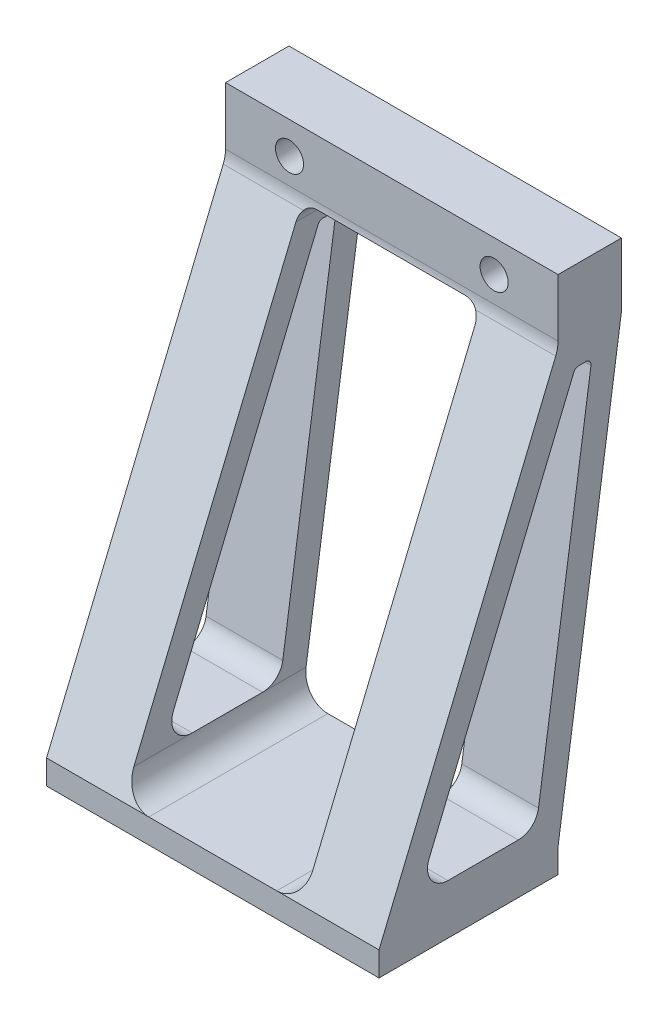
SolidWorks part; units mm, degrees
ref_plane "Front Plane" through (0, 0, 0) normal (0, 0, 1) x (1, 0, 0)
ref_plane "Top Plane" through (0, 0, 0) normal (0, 1, 0) x (1, 0, 0)
ref_plane "Right Plane" through (0, 0, 0) normal (1, 0, 0) x (0, 0, -1)
sketch "Sketch1" plane through (0, 0, 0) normal (1, 0, 0) x (0, 0, -1)
  line L0 (47.3943, 101.6) -> (47.3943, 89.1354)
  line L1 (0, 0) -> (35, 0)
  line L2 (0, 0) -> (0, 4.7625)
  line L4 (35, 101.6) -> (47.3943, 101.6)
  line L5 (35, 0) -> (35, 4.7625)
  line L6 (35, 4.7625) -> (47.3943, 89.1354)
  line L7 (35, 101.6) -> (35, 90.3305)
  line L8 (34.5421, 88.0316) -> (0, 4.7625)
  arc A0 (35, 90.3305) -> (34.5421, 88.0316) centre (29, 90.3305) cw
  dimension "D1" = 6
extrude "Boss-Extrude1" add sketch "Sketch1" along normal blind 65
sketch "Sketch2" plane through (0, 0, 0) normal (0, 0, 1) x (1, 0, 0)
  line L1 (15, 4.7625) -> (50, 4.7625)
  line L2 (15, 4.7625) -> (15, 101.6)
  line L3 (15, 101.6) -> (50, 101.6)
  line L4 (50, 4.7625) -> (50, 101.6)
  line L8 (0, 4.7625) -> (0, 0) construction
  line L9 (65, 0) -> (0, 0) construction
  dimension "D1" = 15
  dimension "D2" = 50
  dimension "D3" = 4.7625
  dimension "D4" = 101.6
extrude "Cut-Extrude1" cut sketch "Sketch2" against normal through all
fillet "Fillet1" radius 5 2 edges at (15, 4.7625, -17.5) (50, 4.7625, -17.5)
sketch "Sketch3" plane through (65, 0, 0) normal (1, 0, 0) x (0, 0, -1)
  line L0 (35, 4.7625) -> (0, 4.7625) construction
  line L1 (47.3943, 89.1354) -> (30.4949, 89.1354) construction
  line L3 (38.0831, 83.5186) -> (9.7823, 15.2952)
  line L4 (13.4771, 9.7625) -> (27.2255, 9.7625)
  line L5 (31.183, 13.1811) -> (41.4379, 82.9901)
  line L6 (39.0068, 84.1354) -> (40.4485, 84.1354)
  line L7 (35, 4.7625) -> (47.3943, 89.1354) construction
  line L8 (34.5421, 88.0316) -> (0, 4.7625) construction
  arc A2 (27.2255, 9.7625) -> (31.183, 13.1811) centre (27.2255, 13.7625) ccw
  arc A3 (9.7823, 15.2952) -> (13.4771, 9.7625) centre (13.4771, 13.7625) ccw
  arc A4 (41.4379, 82.9901) -> (40.4485, 84.1354) centre (40.4485, 83.1354) ccw
  arc A5 (38.0831, 83.5186) -> (39.0068, 84.1354) centre (39.0068, 83.1354) cw
  point P9 (41.6065, 84.1354)
  point P13 (38.3574, 84.1354)
  point P16 (0, 0)
  point P25 (38.1112, 84.1354)
  dimension "D5" = 1
  dimension "D1" = 5
  dimension "D2" = 5
  dimension "D3" = 5
  dimension "D4" = 5
extrude "Cut-Extrude2" cut sketch "Sketch3" against normal through all contours L6 A4 L5 A2 L4 A3 L3 A5
sketch "Sketch4" plane through (15, 0, 0) normal (1, 0, 0) x (0, 0, -1)
  line L0 (47.3943, 101.6) -> (35, 101.6) construction
  line L1 (47.3943, 89.1354) -> (47.3943, 101.6) construction
  line L2 (47.3943, 89.1354) -> (47.3943, 101.6)
  line L3 (47.3943, 101.6) -> (35, 101.6)
  line L7 (35, 101.6) -> (35, 90.3305)
  line L8 (47.3943, 89.1354) -> (34.8798, 89.1354)
  arc A3 (34.5421, 88.0316) -> (35, 90.3305) centre (29, 90.3305) ccw construction
  arc A4 (34.8798, 89.1354) -> (35, 90.3305) centre (29, 90.3305) ccw
extrude "Boss-Extrude2" add sketch "Sketch4" along normal up to surface (35 mm away) up to face at (50, 58.1082, -31.8148)
sketch "Sketch5" plane through (0, 0, -47.3943) normal (0, 0, -1) x (-1, 0, 0)
  line L0 (-65, 89.1354) -> (0, 89.1354)
  line L1 (0, 89.1354) -> (0, 101.6)
  line L2 (0, 101.6) -> (-65, 101.6)
  line L3 (-65, 101.6) -> (-65, 89.1354)
  circle A2 centre (-12.5, 95.3677) radius 2.75
  circle A3 centre (-52.5, 95.3677) radius 2.75
  point P8 (-65, 101.6)
extrude "Cut-Extrude3" cut sketch "Sketch5" against normal through all contours A3 | A2
fillet "Fillet3" radius 3 2 edges at (15, 89.1354, -41.137) (50, 89.1354, -41.137)
